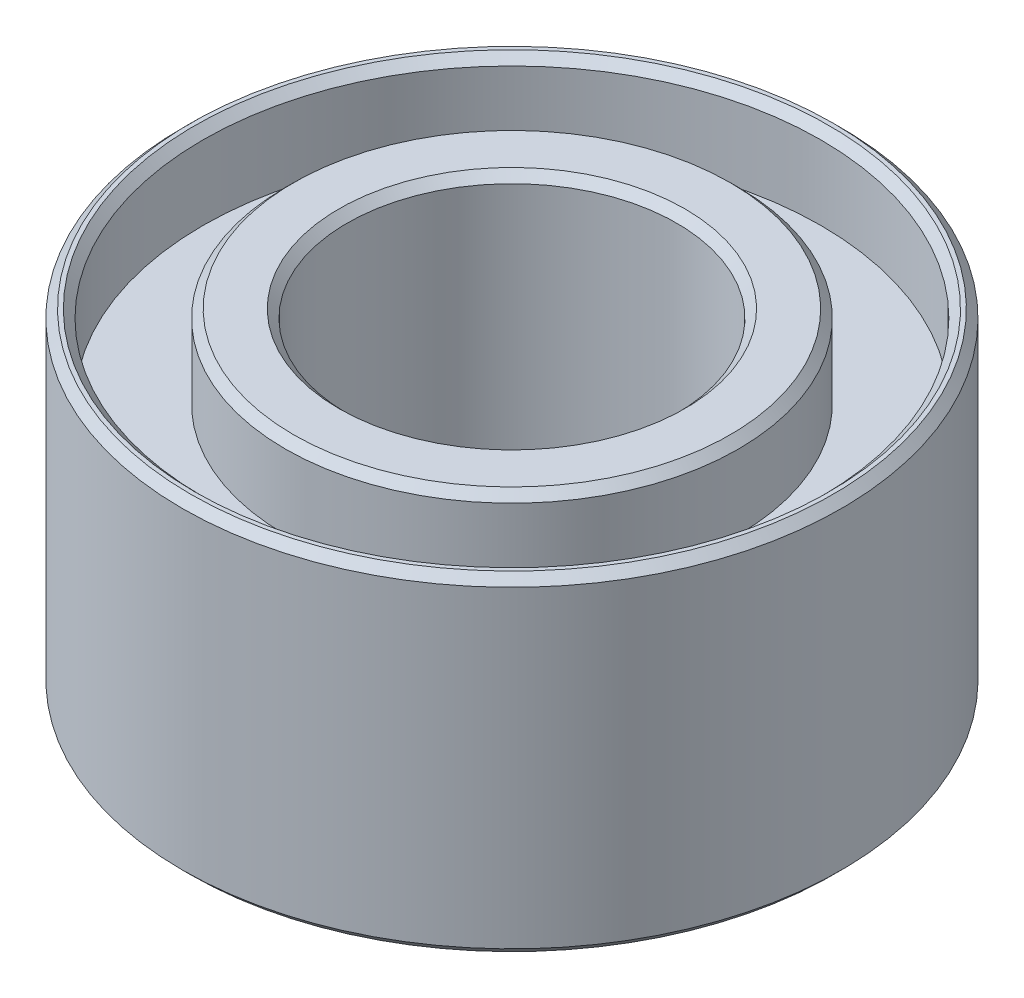
SolidWorks part; units mm, degrees
ref_plane "Front Plane" through (0, 0, 0) normal (0, 0, 1) x (1, 0, 0)
ref_plane "Top Plane" through (0, 0, 0) normal (0, 1, 0) x (1, 0, 0)
ref_plane "Right Plane" through (0, 0, 0) normal (1, 0, 0) x (0, 0, -1)
sketch "Sketch1" plane through (0, 0, 0) normal (0, 1, 0) x (1, 0, 0)
  circle A0 centre (0, 0) radius 4
  circle A1 centre (0, 0) radius 2
  dimension "D1" = 8
  dimension "D2" = 4
extrude "Boss-Extrude1" add sketch "Sketch1" along normal blind 4
sketch "Sketch2" plane through (0, 4, 0) normal (0, 1, 0) x (1, 0, 0)
  circle A0 centre (0, 0) radius 2.75
  circle A1 centre (0, 0) radius 3.75
  dimension "D1" = 7.5
  dimension "D2" = 5.5
extrude "Cut-Extrude1" cut sketch "Sketch2" against normal blind 1
sketch "Sketch3" plane through (0, 0, 0) normal (0, -1, 0) x (1, 0, 0)
  circle A0 centre (0, 0) radius 3.75
  circle A1 centre (0, 0) radius 2.75
  dimension "D1" = 5.5
  dimension "D2" = 7.5
extrude "Cut-Extrude2" cut sketch "Sketch3" against normal blind 1
chamfer "Chamfer1" distance 0.1 angle 45 8 edges at (0, 0, 4) (0, 0, -3.75) (0, 0, -2.75) (0, 0, 2) (0, 4, 2.75) (0, 4, 2) (0, 4, 4) (0, 4, 3.75)
